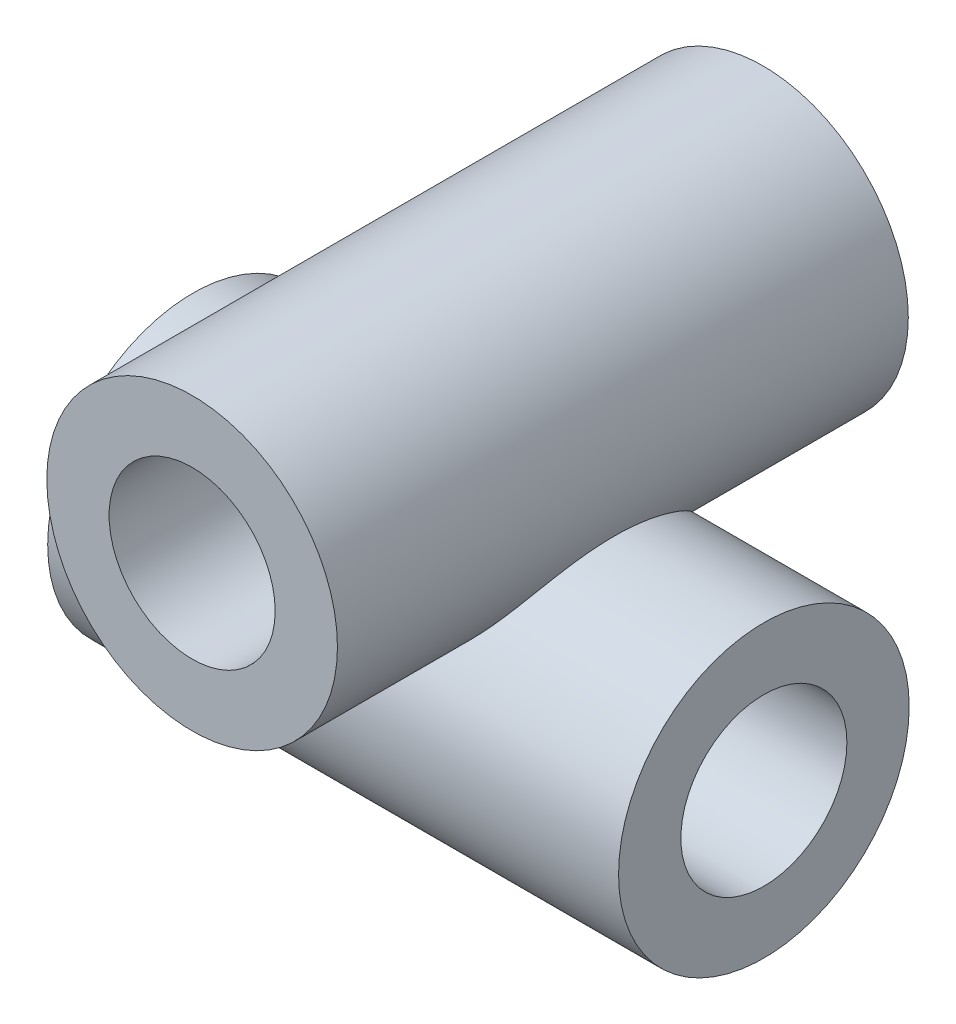
SolidWorks part; units mm, degrees
ref_plane "Front Plane" through (0, 0, 0) normal (0, 0, 1) x (1, 0, 0)
ref_plane "Top Plane" through (0, 0, 0) normal (0, 1, 0) x (1, 0, 0)
ref_plane "Right Plane" through (0, 0, 0) normal (1, 0, 0) x (0, 0, -1)
sketch "Sketch1" plane through (0, 0, 0) normal (0, 0, 1) x (1, 0, 0)
  circle A0 centre (0, 0) radius 28
  dimension "D1" = 56
extrude "Boss-Extrude1" add sketch "Sketch1" along normal blind 110
sketch "Sketch3" plane through (0, 0, 0) normal (1, 0, 0) x (0, 0, -1)
  line L0 (-110, 0) -> (0, 0) construction
  circle A0 centre (-54.8313, -38) radius 28
  dimension "D1" = 56
  dimension "D2" = 38
extrude "Boss-Extrude2" add sketch "Sketch3" along normal mid plane 110
sketch "Sketch4" plane through (0, 0, 110) normal (0, 0, 1) x (1, 0, 0)
  circle A0 centre (0, 0) radius 16
  dimension "D1" = 32
extrude "Cut-Extrude1" cut sketch "Sketch4" against normal through all
sketch "Sketch6" plane through (55, 0, 0) normal (1, 0, 0) x (0, 0, -1)
  circle A0 centre (-54.8313, -38) radius 16
  dimension "D1" = 32
extrude "Cut-Extrude2" cut sketch "Sketch6" against normal through all
